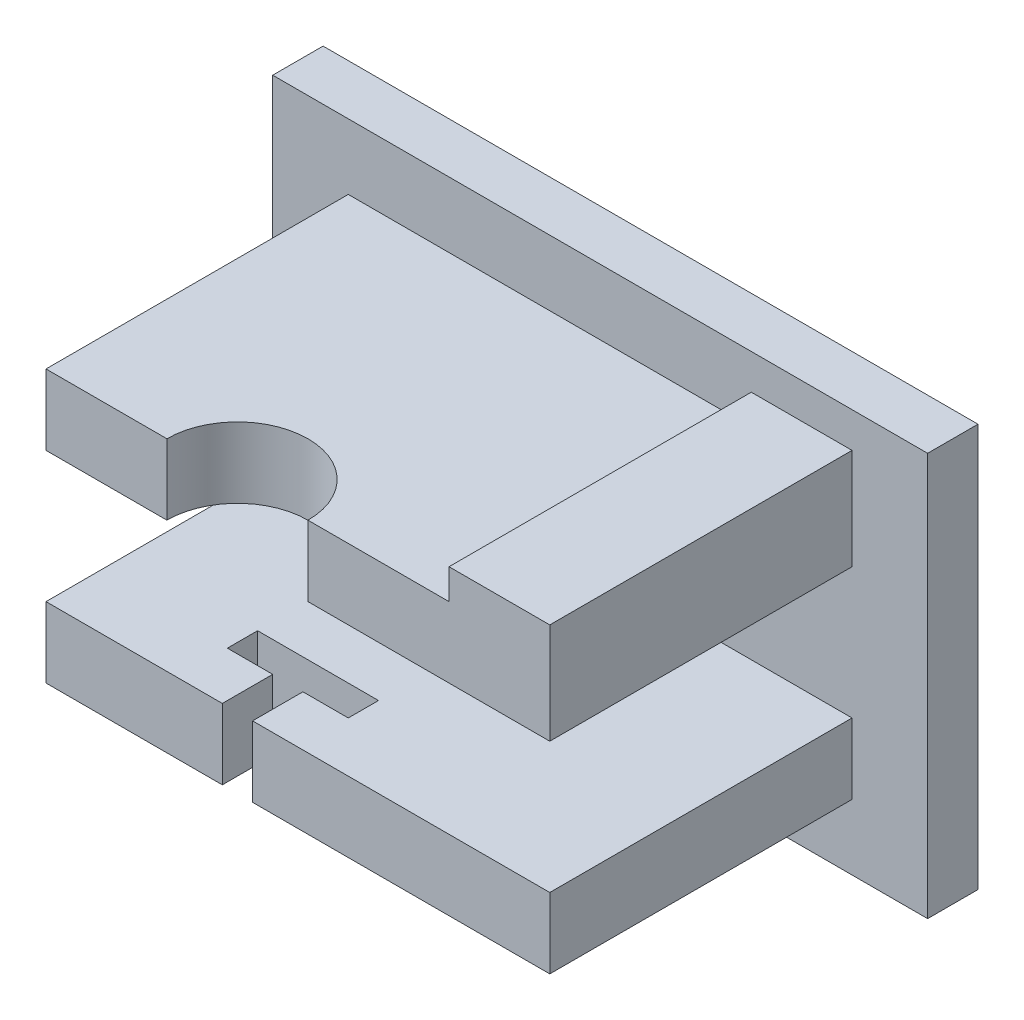
SolidWorks part; units mm, degrees
ref_plane "Спереди" through (0, 0, 0) normal (0, 0, 1) x (1, 0, 0)
ref_plane "Сверху" through (0, 0, 0) normal (0, 1, 0) x (1, 0, 0)
ref_plane "Справа" through (0, 0, 0) normal (1, 0, 0) x (0, 0, -1)
sketch "Эскиз1" plane through (0, 0, 0) normal (0, 0, 1) x (1, 0, 0)
  line L1 (-32.5, -20) -> (32.5, -20)
  line L2 (-32.5, -20) -> (-32.5, 20)
  line L3 (-32.5, 20) -> (32.5, 20)
  line L4 (32.5, -20) -> (32.5, 20)
  line L5 (-32.5, -20) -> (32.5, 20) construction
  line L6 (-32.5, 20) -> (32.5, -20) construction
  point P0 (0, 0)
  dimension "D1" = 65
  dimension "D2" = 40
extrude "Бобышка-Вытянуть1" add sketch "Эскиз1" along normal blind 5
sketch "Эскиз2" plane through (0, 0, 5) normal (0, 0, 1) x (1, 0, 0)
  line L0 (-32.5, 0) -> (32.5, 0) construction
  line L1 (-32.5, 20) -> (-32.5, -20) construction
  line L2 (32.5, -20) -> (32.5, 20) construction
  line L3 (0, 0) -> (0, -20) construction
  line L5 (-32.5, -20) -> (32.5, -20) construction
  line L6 (0, 0) -> (0, 20) construction
  line L7 (-25, -13.5) -> (25, -13.5)
  line L8 (-25, -13.5) -> (-25, -6.5)
  line L9 (-25, -6.5) -> (25, -6.5)
  line L10 (25, -13.5) -> (25, -6.5)
  line L11 (-25, -13.5) -> (25, -6.5) construction
  line L12 (-25, -6.5) -> (25, -13.5) construction
  line L13 (32.5, 20) -> (-32.5, 20) construction
  line L14 (0, 10) -> (-32.5, 10) construction
  line L15 (25, 13.5) -> (25, 16.5)
  line L16 (25, 6.5) -> (-25, 6.5)
  line L17 (25, 6.5) -> (25, 13.5)
  line L18 (25, 13.5) -> (-25, 13.5)
  line L19 (-25, 6.5) -> (-25, 13.5)
  line L20 (25, 6.5) -> (-25, 13.5) construction
  line L21 (25, 13.5) -> (-25, 6.5) construction
  line L22 (25, 16.5) -> (15, 16.5)
  line L23 (15, 16.5) -> (15, 13.5)
  point P8 (0, -10)
  point P21 (0, 10)
  dimension "D1" = 7
  dimension "D2" = 50
  dimension "D3" = 50
  dimension "D4" = 10
  dimension "D5" = 3
extrude "Бобышка-Вытянуть2" add sketch "Эскиз2" along normal blind 30 contours L19 L16 L17 L18 | L22 L23 L18 L15 | L7 L10 L9 L8
sketch "Эскиз4" plane through (0, 13.5, 0) normal (0, 1, 0) x (1, 0, 0)
  line L0 (15, -35) -> (-25, -35) construction
  line L1 (-25, -35) -> (-25, -5) construction
  circle A0 centre (-6, -35) radius 7
  dimension "D1" = 14
  dimension "D2" = 19
extrude "Вырез-Вытянуть1" cut sketch "Эскиз4" against normal up to surface (7 mm away) up to face at (0, 6.5, 20)
sketch "Эскиз7" plane through (0, -13.5, 0) normal (0, -1, 0) x (1, 0, 0)
  line L0 (-6, 28.5) -> (-6, 35) construction
  line L2 (-12, 27) -> (0, 27)
  line L3 (-12, 27) -> (-12, 30)
  line L4 (-12, 30) -> (0, 30)
  line L5 (0, 27) -> (0, 30)
  line L6 (-12, 27) -> (0, 30) construction
  line L7 (-12, 30) -> (0, 27) construction
  line L8 (-25, 35) -> (25, 35) construction
  line L10 (-7.5, 30) -> (-4.5, 30)
  line L11 (-7.5, 30) -> (-7.5, 35)
  line L12 (-7.5, 35) -> (-4.5, 35)
  line L13 (-4.5, 30) -> (-4.5, 35)
  line L14 (-7.5, 30) -> (-4.5, 35) construction
  line L15 (-7.5, 35) -> (-4.5, 30) construction
  point P0 (-6, 28.5)
  point P9 (-6, 32.5)
  point P14 (-6, 35)
  dimension "D1" = 3
  dimension "D2" = 5
  dimension "D3" = 12
extrude "Вырез-Вытянуть3" cut sketch "Эскиз7" against normal up to surface (7 mm away) contours L2 L5 L4 L3 | L13 L12 L11 L10 up to face at (0, -6.5, 20)
